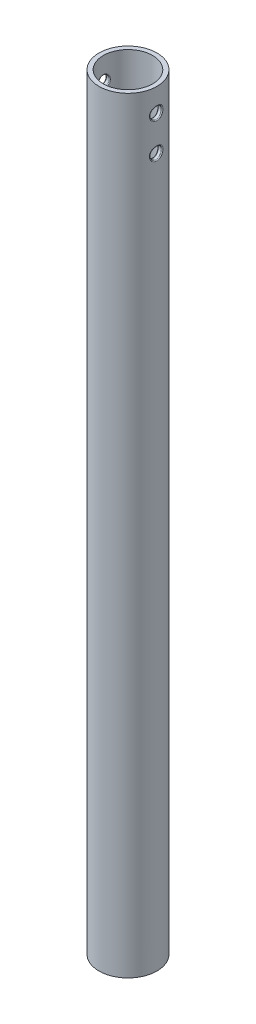
SolidWorks part; units mm, degrees
material "1023 Carbon Steel Sheet (SS)"
ref_plane "Front Plane" through (0, 0, 0) normal (0, 0, 1) x (1, 0, 0)
ref_plane "Top Plane" through (0, 0, 0) normal (0, 1, 0) x (1, 0, 0)
ref_plane "Right Plane" through (0, 0, 0) normal (1, 0, 0) x (0, 0, -1)
sketch "Sketch1" plane through (0, 0, 0) normal (0, 1, 0) x (1, 0, 0)
  circle A0 centre (0, 0) radius 4.25
  circle A2 centre (0, 0) radius 5
  dimension "D1" = 10
  dimension "D2" = 0.75
extrude "Boss-Extrude1" add sketch "Sketch1" along normal blind 132.21
sketch "Sketch2" plane through (0, 0, 0) normal (1, 0, 0) x (0, 0, -1)
  line L1 (5, 132.21) -> (-5, 132.21) construction
  circle A0 centre (0, 128.21) radius 1
  circle A1 centre (0, 122.21) radius 1
  dimension "D3" = 2
  dimension "D1" = 4
  dimension "D2" = 6
extrude "Cut-Extrude1" cut sketch "Sketch2" against normal through all both and the other way through all
fillet "Fillet1" radius 0.15 8 edges at (-4.1355, 122.0104, 0.9799) (4.1355, 122.4096, 0.9799) (-4.1355, 128.0104, 0.9799) (4.1355, 128.4096, 0.9799) (-4.9034, 122.0021, 0.9782) (4.9034, 122.4179, 0.9782) (-4.9034, 128.0021, 0.9782) (4.9034, 128.4179, 0.9782)
